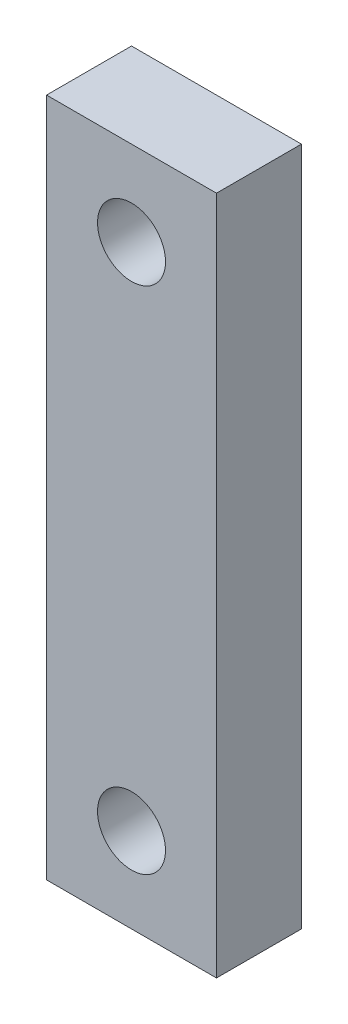
SolidWorks part; units mm, degrees
ref_plane "Front" through (0, 0, 0) normal (0, 0, 1) x (1, 0, 0)
ref_plane "Top" through (0, 0, 0) normal (0, 1, 0) x (1, 0, 0)
ref_plane "Right" through (0, 0, 0) normal (1, 0, 0) x (0, 0, -1)
sketch "Esquisse1" plane through (0, 0, 0) normal (0, 0, 1) x (1, 0, 0)
  line L1 (0, 0) -> (20, 0)
  line L2 (0, 0) -> (0, 80)
  line L3 (0, 80) -> (20, 80)
  line L4 (20, 0) -> (20, 80)
  dimension "D1" = 20
  dimension "D2" = 80
extrude "Boss.-Extru.1" add sketch "Esquisse1" along normal blind 10
sketch "Esquisse2" plane through (0, 0, 10) normal (0, 0, 1) x (1, 0, 0)
  line L0 (10, 0) -> (10, 80) construction
  line L1 (0, 0) -> (20, 0) construction
  line L2 (20, 80) -> (0, 80) construction
  line L3 (0, 40) -> (20, 40) construction
  line L4 (0, 80) -> (0, 0) construction
  line L5 (20, 0) -> (20, 80) construction
  circle A0 centre (10, 70) radius 4
  circle A1 centre (10, 10) radius 4
  dimension "D1" = 8
  dimension "D2" = 10
extrude "Enlèv. mat.-Extru.1" cut sketch "Esquisse2" against normal through all
